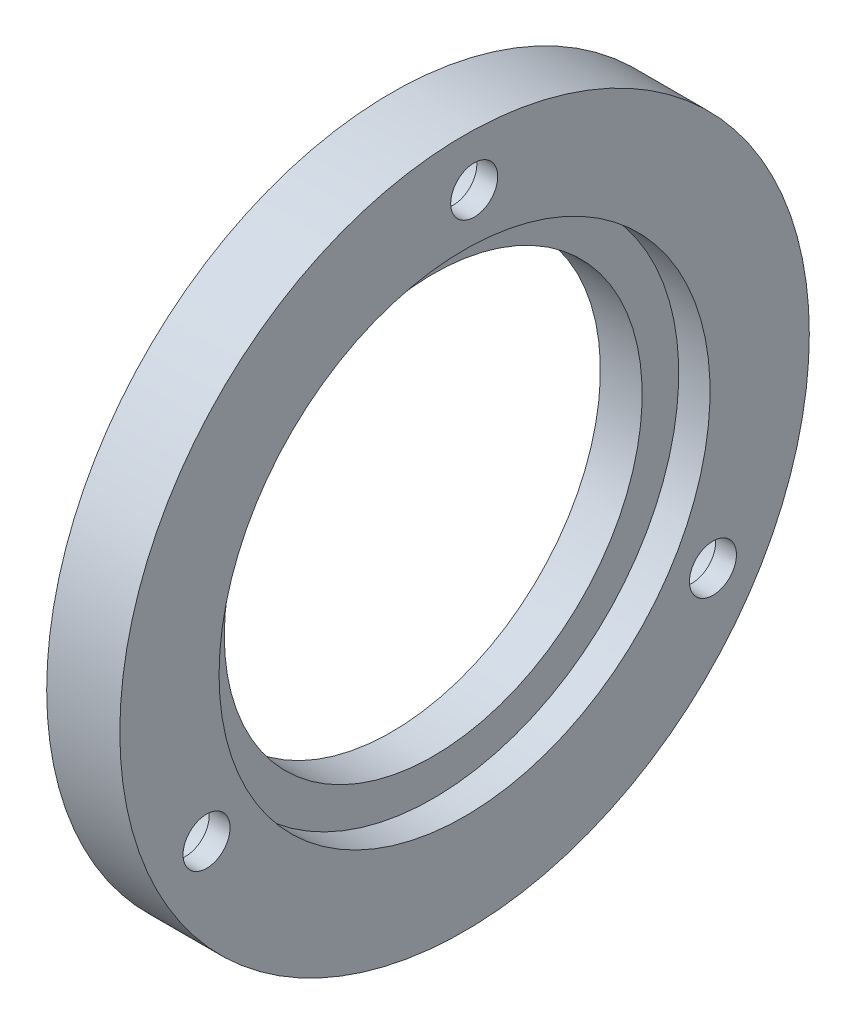
SolidWorks part; units mm, degrees
material "Alliage 1060"
ref_plane "Plan de face" through (0, 0, 0) normal (0, 0, 1) x (1, 0, 0)
ref_plane "Plan de dessus" through (0, 0, 0) normal (0, 1, 0) x (1, 0, 0)
ref_plane "Plan de droite" through (0, 0, 0) normal (1, 0, 0) x (0, 0, -1)
sketch "Esquisse1" plane through (0, 0, 0) normal (0, 0, 1) x (1, 0, 0)
  line L0 (-15.1382, 0) -> (27.7534, 0) construction
  line L1 (0, 20) -> (0, 33)
  line L2 (0, 33) -> (7, 33)
  line L3 (7, 33) -> (7, 23.5)
  line L4 (7, 23.5) -> (4, 23.5)
  line L5 (4, 23.5) -> (4, 20)
  line L6 (4, 20) -> (0, 20)
  dimension "D1" = 66
  dimension "D2" = 40
  dimension "D3" = 47
  dimension "D4" = 7
  dimension "D5" = 3
revolve "Révolution1" add sketch "Esquisse1" angle 360 about L0
hole_wizard "Chambrage pour vis à tête hexagonale M41" positions "Esquisse3D1" profile "Esquisse2" counterbore size "M4" standard "ISO" end condition through all
sketch3d "Esquisse3D1"
  point P0 (0, 27.9848, -0.9219)
  dimension "D1" = 28
sketch "Esquisse2" plane through (0, 27.9848, -0.9219) normal (0, 1, 0) x (0, 0, 1)
  line L0 (0, 0) -> (0, 7)
  line L1 (0, 7) -> (2.25, 7)
  line L3 (2.25, 7) -> (2.25, 5)
  line L4 (2.25, 5) -> (4, 5)
  line L5 (4, 5) -> (4, 0)
  line L7 (4, 0) -> (0, 0)
  line L11 (0, -6.35) -> (0, 107.95) construction
  dimension "Diamètre du perçage jusqu'au prochain" = 4.5
  dimension "Profondeur du perçage jusqu'au prochain" = 7
  dimension "Diamètre du chambrage" = 8
  dimension "Profondeur du chambrage" = 5
pattern_circular "Répétition circulaire1" count 3 over 360 about axis through (0, 0, 0) along (1, 0, 0) of "Chambrage pour vis à tête hexagonale M41"
